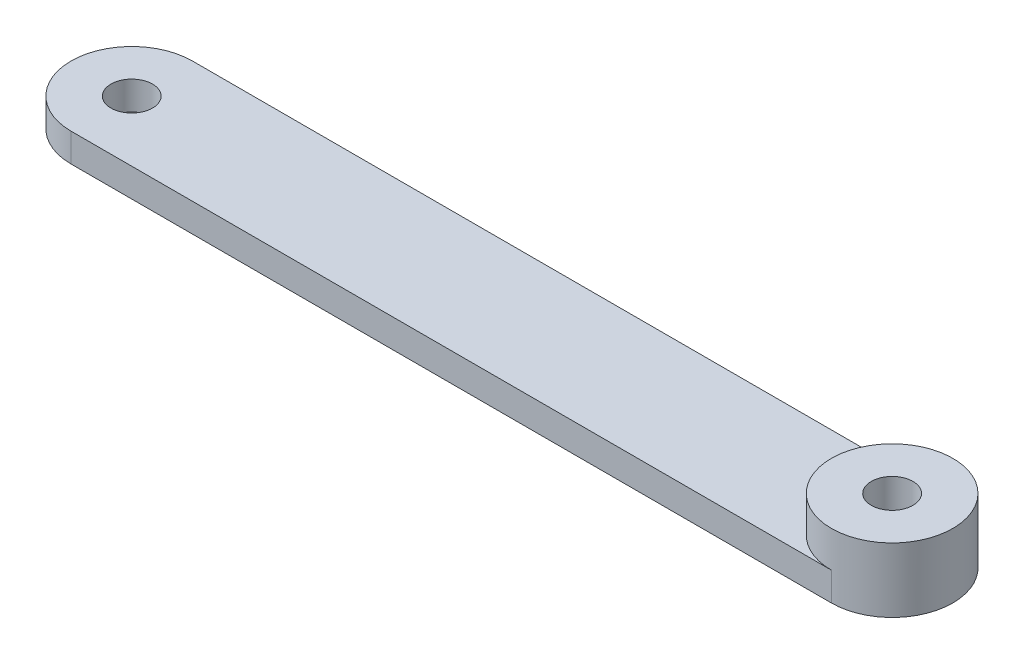
SolidWorks part; units mm, degrees
material "PET"
ref_plane "Front" through (0, 0, 0) normal (0, 0, 1) x (1, 0, 0)
ref_plane "Top" through (0, 0, 0) normal (0, 1, 0) x (1, 0, 0)
ref_plane "Right" through (0, 0, 0) normal (1, 0, 0) x (0, 0, -1)
sketch "Sketch1" plane through (0, 0, 0) normal (0, 1, 0) x (1, 0, 0)
  line L1 (-23.1719, 5.6259) -> (56.3301, 5.6259)
  line L3 (-23.1719, -7.0741) -> (56.3301, -7.0741)
  line L5 (-23.1719, 5.6259) -> (56.3301, -7.0741) construction
  line L6 (-23.1719, -7.0741) -> (56.3301, 5.6259) construction
  arc A0 (-23.1719, 5.6259) -> (-23.1719, -7.0741) centre (-23.1719, -0.7241) ccw
  arc A1 (56.3301, 5.6259) -> (56.3301, -7.0741) centre (56.3301, -0.7241) cw
  point P4 (16.5791, -0.7241)
  dimension "D1" = 6.35
  dimension "D2" = 79.502
  dimension "D3" = 12.7
extrude "Boss-Extrude1" add sketch "Sketch1" along normal blind 2.975
sketch "Sketch2" plane through (0, 2.975, 0) normal (0, 1, 0) x (1, 0, 0)
  circle A0 centre (-23.1719, -0.7241) radius 2.175
  circle A2 centre (56.3301, -0.7241) radius 2.175
  dimension "D1" = 4.35
  dimension "D2" = 79.502
  dimension "D3" = 4.35
extrude "Cut-Extrude1" cut sketch "Sketch2" against normal blind 12.7
sketch "Sketch3" plane through (0, 2.975, 0) normal (0, 1, 0) x (1, 0, 0)
  circle A0 centre (56.3301, -0.7241) radius 2.175
  arc A2 (56.3301, 5.6259) -> (56.3301, -7.0741) centre (56.3301, -0.7241) cw
  arc A3 (56.3301, 5.6259) -> (56.3301, -7.0741) centre (56.3301, -0.7241) ccw
extrude "Boss-Extrude2" add sketch "Sketch3" along normal blind 3.775
